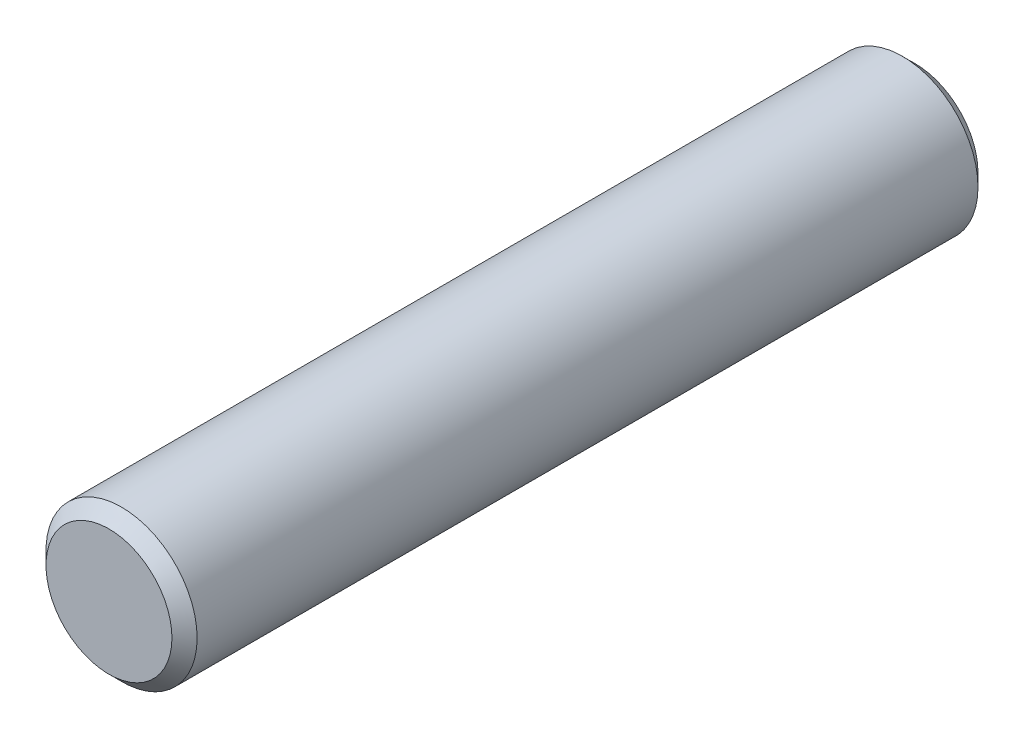
SolidWorks part; units mm, degrees
ref_plane "Front Plane" through (0, 0, 0) normal (0, 0, 1) x (1, 0, 0)
ref_plane "Top Plane" through (0, 0, 0) normal (0, 1, 0) x (1, 0, 0)
ref_plane "Right Plane" through (0, 0, 0) normal (1, 0, 0) x (0, 0, -1)
sketch "Sketch1" plane through (0, 0, 0) normal (0, 0, 1) x (1, 0, 0)
  circle A0 centre (0, 0) radius 3
extrude "Boss-Extrude1" add sketch "Sketch1" along normal blind 32
chamfer "Chamfer1" distance 0.5 angle 45 2 edges at (3, 0, 0) (3, 0, 32)
